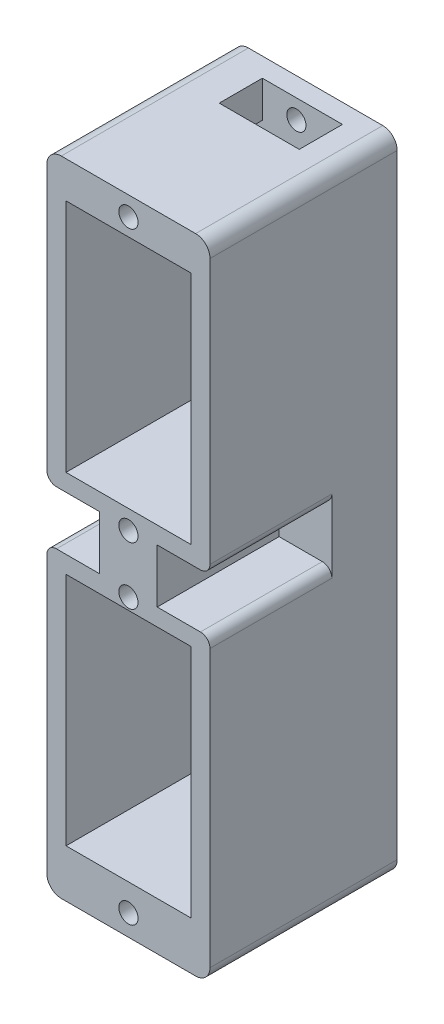
SolidWorks part; units mm, degrees
ref_plane "Front Plane" through (0, 0, 0) normal (0, 0, 1) x (1, 0, 0)
ref_plane "Top Plane" through (0, 0, 0) normal (0, 1, 0) x (1, 0, 0)
ref_plane "Right Plane" through (0, 0, 0) normal (1, 0, 0) x (0, 0, -1)
other "Graphic1"
ref_plane "Plane1" through (0, 0, 30) normal (0, 0, 1) x (1, 0, 0)
sketch "Sketch4" plane through (0, 0, 30) normal (0, 0, 1) x (1, 0, 0)
  line L1 (-192.737, 275.5472) -> (-175.737, 275.5472)
  line L2 (-192.737, 275.5472) -> (-192.737, 208.5472)
  line L3 (-192.737, 208.5472) -> (-175.737, 208.5472)
  line L4 (-175.737, 275.5472) -> (-175.737, 208.5472)
  dimension "D1" = 67
  dimension "D2" = 17
extrude "Boss-Extrude1" add sketch "Sketch4" along normal blind 19.5
fillet "Fillet1" radius 1.5 4 edges at (-192.737, 275.5472, 39.75) (-175.737, 275.5472, 39.75) (-192.737, 208.5472, 39.75) (-175.737, 208.5472, 39.75)
sketch "Sketch5" plane through (0, 0, 49.5) normal (0, 0, 1) x (1, 0, 0)
  line L0 (-177.237, 275.5472) -> (-191.237, 275.5472) construction
  line L1 (-190.737, 271.7472) -> (-177.737, 271.7472)
  line L2 (-190.737, 271.7472) -> (-190.737, 247.2472)
  line L3 (-190.737, 247.2472) -> (-177.737, 247.2472)
  line L4 (-177.737, 271.7472) -> (-177.737, 247.2472)
  line L5 (-175.737, 210.0472) -> (-175.737, 274.0472) construction
  line L6 (-191.237, 208.5472) -> (-177.237, 208.5472) construction
  line L7 (-190.737, 238.0472) -> (-177.737, 238.0472)
  line L8 (-190.737, 238.0472) -> (-190.737, 213.5472)
  line L9 (-190.737, 213.5472) -> (-177.737, 213.5472)
  line L10 (-177.737, 238.0472) -> (-177.737, 213.5472)
  point P6 (-184.237, 275.5472)
  dimension "D1" = 13
  dimension "D2" = 24.5
  dimension "D3" = 3.8
  dimension "D4" = 2
  dimension "D5" = 24.5
  dimension "D6" = 5
  dimension "D7" = 2
extrude "Cut-Extrude1" cut sketch "Sketch5" against normal blind 17.5
sketch "Sketch6" plane through (0, 0, 49.5) normal (0, 0, 1) x (1, 0, 0)
  line L0 (-192.737, 274.0472) -> (-192.737, 210.0472) construction
  line L1 (-187.237, 245.4472) -> (-192.737, 245.4472)
  line L2 (-187.237, 245.4472) -> (-187.237, 239.8472)
  line L3 (-187.237, 239.8472) -> (-192.737, 239.8472)
  line L4 (-192.737, 245.4472) -> (-192.737, 239.8472)
  line L5 (-175.737, 210.0472) -> (-175.737, 274.0472) construction
  line L6 (-181.237, 245.4472) -> (-175.737, 245.4472)
  line L7 (-181.237, 245.4472) -> (-181.237, 239.8472)
  line L8 (-181.237, 239.8472) -> (-175.737, 239.8472)
  line L9 (-175.737, 245.4472) -> (-175.737, 239.8472)
  line L10 (-190.737, 247.2472) -> (-177.737, 247.2472) construction
  line L11 (-177.737, 238.0472) -> (-190.737, 238.0472) construction
  dimension "D1" = 6
  dimension "D2" = 1.8
  dimension "D3" = 1.8
extrude "Cut-Extrude2" cut sketch "Sketch6" against normal blind 12.7
fillet "Fillet2" radius 1 4 edges at (-175.737, 239.8472, 43.15) (-175.737, 245.4472, 43.15) (-192.737, 239.8472, 43.15) (-192.737, 245.4472, 43.15)
sketch "Sketch7" plane through (0, 0, 49.5) normal (0, 0, 1) x (1, 0, 0)
  line L0 (-175.737, 246.4472) -> (-175.737, 274.0472) construction
  line L1 (-190.737, 247.2472) -> (-177.737, 247.2472) construction
  line L2 (-177.237, 275.5472) -> (-191.237, 275.5472) construction
  circle A0 centre (-184.237, 273.5472) radius 1
  circle A1 centre (-184.237, 210.7472) radius 1
  circle A2 centre (-184.237, 245.2472) radius 1
  circle A3 centre (-184.237, 239.2472) radius 1
  dimension "D1" = 6
  dimension "D2" = 8.5
  dimension "D3" = 2
  dimension "D4" = 28.5
  dimension "D5" = 2
extrude "Cut-Extrude3" cut sketch "Sketch7" against normal through all
sketch "Sketch8" plane through (0, 208.5472, 0) normal (0, -1, 0) x (-1, 0, 0)
  line L0 (191.237, -30) -> (177.237, -30) construction
  line L1 (188.937, -36.5) -> (179.437, -36.5)
  line L2 (188.937, -36.5) -> (188.937, -32)
  line L3 (188.937, -32) -> (179.437, -32)
  line L4 (179.437, -36.5) -> (179.437, -32)
  line L5 (192.737, -30) -> (192.737, -49.5) construction
  dimension "D1" = 9.5
  dimension "D2" = 4.5
  dimension "D3" = 2
  dimension "D4" = 3.8
extrude "Cut-Extrude4" cut sketch "Sketch8" against normal blind 5
sketch "Sketch9" plane through (0, 275.5472, 0) normal (0, 1, 0) x (1, 0, 0)
  line L1 (-179.437, -36.5) -> (-187.7805, -36.5)
  line L2 (-179.437, -36.5) -> (-179.437, -32)
  line L3 (-179.437, -32) -> (-187.7805, -32)
  line L4 (-187.7805, -36.5) -> (-187.7805, -32)
extrude "Cut-Extrude5" cut sketch "Sketch9" against normal blind 5
